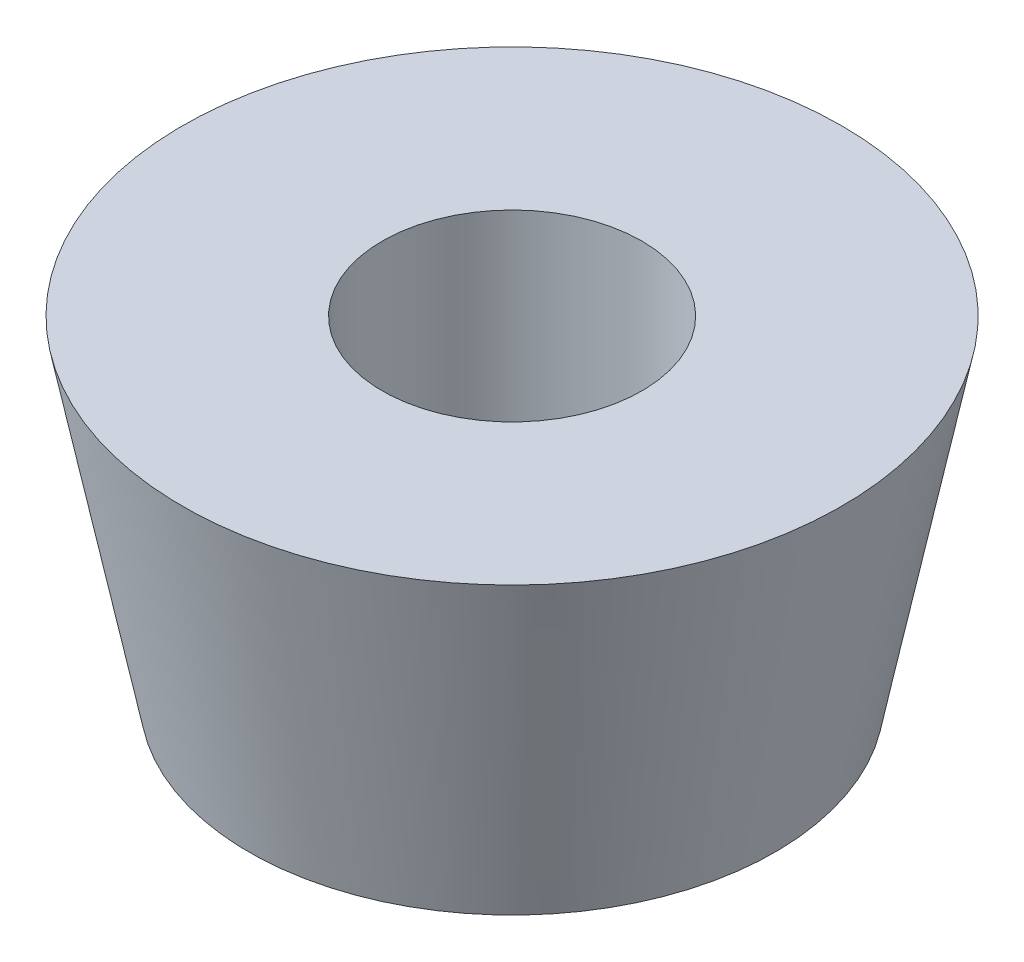
SolidWorks part; units mm, degrees
material "Titanium"
ref_plane "Front Plane" through (0, 0, 0) normal (0, 0, 1) x (1, 0, 0)
ref_plane "Top Plane" through (0, 0, 0) normal (0, 1, 0) x (1, 0, 0)
ref_plane "Right Plane" through (0, 0, 0) normal (1, 0, 0) x (0, 0, -1)
sketch "Sketch1" plane through (0, 0, 0) normal (0, 0, 1) x (1, 0, 0)
  line L0 (0, 0) -> (0, 5) construction
  line L1 (1.95, 0) -> (3.95, 0)
  line L2 (3.95, 0) -> (4.95, 5)
  line L3 (4.95, 5) -> (1.95, 5)
  line L4 (1.95, 5) -> (1.95, 0)
  dimension "D1" = 5
  dimension "D2" = 1.95
  dimension "D3" = 3
  dimension "D4" = 2
revolve "Revolve1" add sketch "Sketch1" angle 360 about L0
